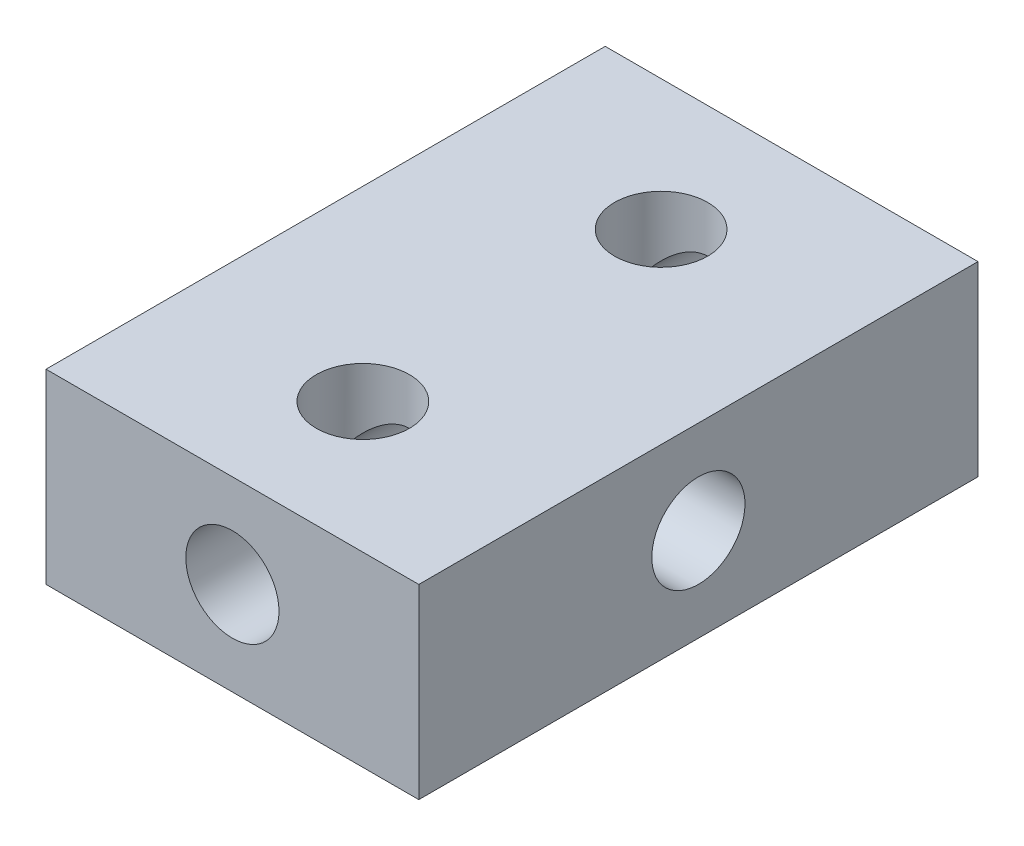
SolidWorks part; units mm, degrees
ref_plane "Plan de face" through (0, 0, 0) normal (0, 0, 1) x (1, 0, 0)
ref_plane "Plan de dessus" through (0, 0, 0) normal (0, 1, 0) x (1, 0, 0)
ref_plane "Plan de droite" through (0, 0, 0) normal (1, 0, 0) x (0, 0, -1)
sketch "Esquisse1" plane through (0, 0, 0) normal (0, 0, 1) x (1, 0, 0)
  line L1 (0, 5) -> (10, 5)
  line L2 (0, 5) -> (0, 0)
  line L3 (0, 0) -> (10, 0)
  line L4 (10, 5) -> (10, 0)
  dimension "D1" = 10
  dimension "D2" = 5
extrude "Extrusion1" add sketch "Esquisse1" along normal blind 15
hole_wizard "Trou taraudé M31" positions "Esquisse3" profile "Esquisse2" tap size "M3" standard "ISO" end condition through all
sketch "Esquisse3" plane through (0, 0, 15) normal (0, 0, 1) x (1, 0, 0)
  line L0 (0, 5) -> (10, 0) construction
  point P0 (5, 2.5)
sketch "Esquisse2" plane through (5, 2.5, 15) normal (1, 0, 0) x (0, -1, 0)
  line L0 (0, 0) -> (0, 15)
  line L1 (0, 15) -> (1.25, 15)
  line L2 (1.25, 15) -> (1.25, 0)
  line L5 (1.25, 0) -> (0, 0)
  line L11 (0, -6.35) -> (0, 107.95) construction
  dimension "Diamètre du trou pour taraudage jusqu'au prochain" = 2.5
  dimension "Profondeur du trou pour taraudage jusqu'au prochain" = 15
cosmetic thread "Filetage de perçage1" parameters "D2"=3
hole_wizard "Trou taraudé M32" positions "Esquisse5" profile "Esquisse6" tap size "M3" standard "ISO" end condition through all
sketch "Esquisse5" plane through (10, 0, 0) normal (1, 0, 0) x (0, 0, -1)
  line L0 (-15, 5) -> (0, 0) construction
  point P0 (-7.5, 2.5)
sketch "Esquisse6" plane through (10, 2.5, 7.5) normal (0, 1, 0) x (0, 0, -1)
  line L0 (0, 0) -> (0, 10)
  line L1 (0, 10) -> (1.25, 10)
  line L2 (1.25, 10) -> (1.25, 0)
  line L5 (1.25, 0) -> (0, 0)
  line L11 (0, -6.35) -> (0, 107.95) construction
  dimension "Diamètre du trou pour taraudage jusqu'au prochain" = 2.5
  dimension "Profondeur du trou pour taraudage jusqu'au prochain" = 10
cosmetic thread "Filetage de perçage2" parameters "D2"=3
hole_wizard "Trou taraudé M33" positions "Esquisse8" profile "Esquisse7" tap size "M3" standard "ISO" end condition through all
sketch "Esquisse8" plane through (0, 5, 0) normal (0, 1, 0) x (-1, 0, 0)
  line L0 (-5, 15) -> (-5, 0) construction
  line L1 (-10, 15) -> (0, 15) construction
  line L2 (-10, 0) -> (0, 0) construction
  point P0 (-5, 11.5)
  point P1 (-5, 3.5)
  dimension "D1" = 8
  dimension "D2" = 3.5
sketch "Esquisse7" plane through (5, 5, 11.5) normal (1, 0, 0) x (0, 0, 1)
  line L0 (0, 0) -> (0, 5)
  line L1 (0, 5) -> (1.25, 5)
  line L2 (1.25, 5) -> (1.25, 0)
  line L5 (1.25, 0) -> (0, 0)
  line L11 (0, -6.35) -> (0, 107.95) construction
  dimension "Diamètre du trou pour taraudage jusqu'au prochain" = 2.5
  dimension "Profondeur du trou pour taraudage jusqu'au prochain" = 5
cosmetic thread "Filetage de perçage3" parameters "D2"=3
cosmetic thread "Filetage de perçage4" parameters "D2"=3
